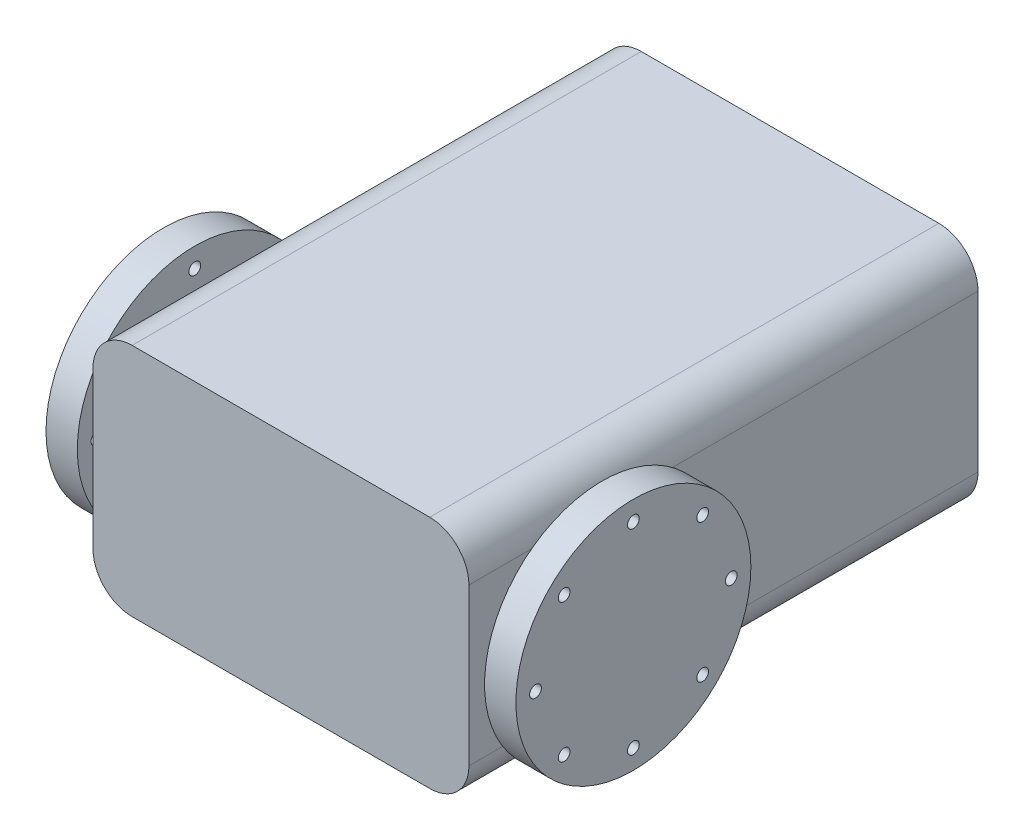
SolidWorks part; units mm, degrees
ref_plane "Front Plane" through (0, 0, 0) normal (0, 0, 1) x (1, 0, 0)
ref_plane "Top Plane" through (0, 0, 0) normal (0, 1, 0) x (1, 0, 0)
ref_plane "Right Plane" through (0, 0, 0) normal (1, 0, 0) x (0, 0, -1)
sketch "Sketch1" plane through (0, 0, 0) normal (0, 0, 1) x (1, 0, 0)
  line L1 (-19, -15) -> (19, -15)
  line L2 (-24, -10) -> (-24, 10)
  line L3 (-19, 15) -> (19, 15)
  line L4 (24, -10) -> (24, 10)
  line L5 (-24, -15) -> (24, 15) construction
  line L6 (-24, 15) -> (24, -15) construction
  arc A0 (19, 15) -> (24, 10) centre (19, 10) cw
  arc A1 (19, -15) -> (24, -10) centre (19, -10) ccw
  arc A2 (-19, -15) -> (-24, -10) centre (-19, -10) cw
  arc A3 (-19, 15) -> (-24, 10) centre (-19, 10) ccw
  point P0 (0, 0)
  dimension "D3" = 5
  dimension "D1" = 48
  dimension "D2" = 30
extrude "Boss-Extrude1" add sketch "Sketch1" along normal mid plane 65
sketch "Sketch2" plane through (24, 0, 0) normal (1, 0, 0) x (0, 0, -1)
  line L0 (-32.5, 0) -> (-17.5, 0) construction
  line L1 (-32.5, -10) -> (-32.5, 10) construction
  circle A0 centre (-17.5, 0) radius 15
  dimension "D2" = 30
  dimension "D1" = 15
extrude "Boss-Extrude2" add sketch "Sketch2" along normal blind 4 from offset 2 separate body
sketch "Sketch3" plane through (26, 0, 0) normal (-1, 0, 0) x (0, 0, 1)
  circle A0 centre (17.5, 0) radius 7.5
  dimension "D1" = 15
extrude "Boss-Extrude3" add sketch "Sketch3" along normal up to surface (50 mm away)
mirror "Mirror3" about plane through (0, 0, 0) normal (1, 0, 0) of "Boss-Extrude3"
sketch "Sketch4" plane through (-26, 0, 0) normal (-1, 0, 0) x (0, 0, 1)
  circle A0 centre (17.5, 0) radius 15
  point P2 (0, 0)
  point P3 (16.5818, 0)
  point P4 (18.32, 0)
  point P5 (17.5, 0)
  dimension "D1" = 30
extrude "Boss-Extrude4" add sketch "Sketch4" along normal blind 4
sketch "Sketch5" plane through (30, 0, 0) normal (1, 0, 0) x (0, 0, -1)
  circle A0 centre (-17.5, 0) radius 12.5
  circle A1 centre (-17.5, 12.5) radius 0.75
  circle A2 centre (-8.6612, 8.8388) radius 0.75
  circle A3 centre (-17.5, 0) radius 12.5
  circle A4 centre (-5, 0) radius 0.75
  circle A5 centre (-17.5, 0) radius 12.5
  circle A6 centre (-8.6612, -8.8388) radius 0.75
  circle A7 centre (-17.5, 0) radius 12.5
  circle A8 centre (-17.5, -12.5) radius 0.75
  circle A9 centre (-17.5, 0) radius 12.5
  circle A10 centre (-26.3388, -8.8388) radius 0.75
  circle A11 centre (-17.5, 0) radius 12.5
  circle A12 centre (-30, 0) radius 0.75
  circle A13 centre (-17.5, 0) radius 12.5
  circle A14 centre (-26.3388, 8.8388) radius 0.75
  circle A15 centre (-17.5, 0) radius 12.5
  point P5 (-17.4593, 0.1966)
  point P36 (-17.5, 0)
  dimension "D1" = 25
  dimension "D2" = 1.5
  dimension "D3" = 8
extrude "Cut-Extrude1" cut sketch "Sketch5" against normal up to surface (4 mm away) contours A14 | A12 | A1 | A2 | A4 | A6 | A8 | A10 up to face at (26, 0, 10)
sketch "Sketch6" plane through (-30, 0, 0) normal (-1, 0, 0) x (0, 0, 1)
  circle A2 centre (17.5, 12.5) radius 0.75
  circle A3 centre (17.5, 0) radius 12.5
  circle A4 centre (17.5, 0) radius 12.5
  circle A5 centre (26.3388, 8.8388) radius 0.75
  circle A6 centre (17.5, 0) radius 12.5
  circle A7 centre (30, 0) radius 0.75
  circle A8 centre (17.5, 0) radius 12.5
  circle A9 centre (26.3388, -8.8388) radius 0.75
  circle A10 centre (17.5, 0) radius 12.5
  circle A11 centre (17.5, -12.5) radius 0.75
  circle A12 centre (17.5, 0) radius 12.5
  circle A13 centre (8.6612, -8.8388) radius 0.75
  circle A14 centre (17.5, 0) radius 12.5
  circle A15 centre (5, 0) radius 0.75
  circle A16 centre (17.5, 0) radius 12.5
  circle A17 centre (8.6612, 8.8388) radius 0.75
  circle A18 centre (17.5, 0) radius 12.5
  point P2 (16.6007, -1.4759)
  point P3 (17.6249, -0.1039)
  point P38 (17.5, 0)
  dimension "D2" = 1.5
  dimension "D1" = 2.5
  dimension "D3" = 8
extrude "Cut-Extrude2" cut sketch "Sketch6" against normal blind 4 contours A17 | A2 | A5 | A7 | A9 | A11 | A13 | A15
